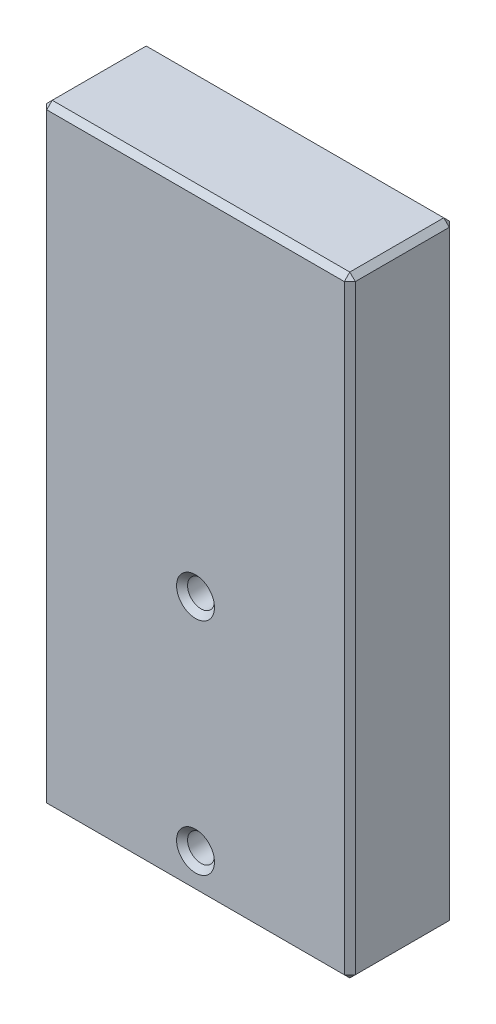
SolidWorks part; units mm, degrees
ref_plane "Front Plane" through (0, 0, 0) normal (0, 0, 1) x (1, 0, 0)
ref_plane "Top Plane" through (0, 0, 0) normal (0, 1, 0) x (1, 0, 0)
ref_plane "Right Plane" through (0, 0, 0) normal (1, 0, 0) x (0, 0, -1)
sketch "Sketch1" plane through (0, 0, 0) normal (0, 0, 1) x (1, 0, 0)
  line L1 (0, 0) -> (28, 0)
  line L2 (0, 0) -> (0, 55.475)
  line L3 (0, 55.475) -> (28, 55.475)
  line L4 (28, 0) -> (28, 55.475)
  dimension "D1" = 28
  dimension "D2" = 55.475
extrude "Boss-Extrude1" add sketch "Sketch1" along normal blind 9.525
sketch "Sketch2" plane through (0, 0, 0) normal (0, -1, 0) x (1, 0, 0)
  line L0 (0, 0) -> (28, 0) construction
  line L1 (0, 9.525) -> (0, 0) construction
  circle A0 centre (5, 4.7625) radius 1.2195
  circle A3 centre (23, 4.7625) radius 1.2195
  dimension "D1" = 2.439
  dimension "D6" = 2.439
  dimension "D2" = 4.7625
  dimension "D3" = 5
  dimension "D4" = 18
extrude "Cut-Extrude1" cut sketch "Sketch2" against normal blind 20
sketch "Sketch3" plane through (0, 0, 9.525) normal (0, 0, 1) x (1, 0, 0)
  line L0 (22.85, 65) -> (5.15, 65)
  line L1 (5.15, 65) -> (5.15, 0)
  line L2 (5.15, 0) -> (22.85, 0)
  line L3 (22.85, 0) -> (22.85, 65)
  line L4 (0, 55.475) -> (0, 0) construction
  circle A0 centre (14, 3.475) radius 1.7
  circle A1 centre (14, 3.475) radius 1.2195
  circle A2 centre (14, 23.475) radius 1.7
  circle A3 centre (14, 23.475) radius 1.2195
  dimension "D6" = 2.439
  dimension "D7" = 3.4
  dimension "D8" = 3.4
  dimension "D9" = 2.439
  dimension "D1" = 3.475
  dimension "D2" = 23.475
  dimension "D3" = 8.85
  dimension "D4" = 65
  dimension "D5" = 17.7
  dimension "D10" = 0
  dimension "D11" = 14
extrude "Cut-Extrude2" cut sketch "Sketch3" against normal through all contours A3 | A1
chamfer "Chamfer1" distance 0.5 angle 45 12 edges at (14, 0, 0) (28, 0, 4.7625) (28, 27.7375, 0) (14, 55.475, 0) (28, 55.475, 4.7625) (28, 27.7375, 9.525) (14, 55.475, 9.525) (14, 0, 9.525) (0, 0, 4.7625) (0, 27.7375, 0) (0, 55.475, 4.7625) (0, 27.7375, 9.525)
chamfer "Chamfer2" distance 0.5 angle 45 6 edges at (23, 0, 3.543) (5, 0, 3.543) (15.2195, 3.475, 0) (15.2195, 23.475, 0) (15.2195, 3.475, 9.525) (15.2195, 23.475, 9.525)
